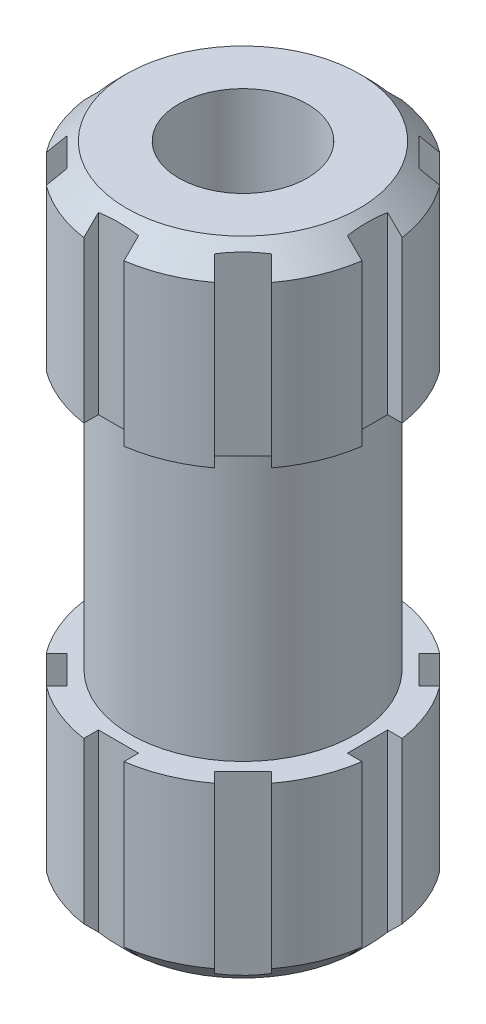
SolidWorks part; units mm, degrees
material "Brass"
ref_plane "Plano frontal" through (0, 0, 0) normal (0, 0, 1) x (1, 0, 0)
ref_plane "Plano superior" through (0, 0, 0) normal (0, 1, 0) x (1, 0, 0)
ref_plane "Plano direito" through (0, 0, 0) normal (1, 0, 0) x (0, 0, -1)
sketch "Esboço2" plane through (0, 0, 0) normal (0, 0, 1) x (1, 0, 0)
  line L0 (0, 0) -> (0, 8) construction
  line L1 (0, 8) -> (1.75, 8)
  line L2 (1.75, 8) -> (1.75, 5.7)
  line L3 (1.75, 5.7) -> (1.4, 5.7)
  line L4 (1.4, 5.7) -> (1.4, 2.3)
  line L5 (1.4, 2.3) -> (1.75, 2.3)
  line L6 (1.75, 2.3) -> (1.75, 0)
  line L7 (0, 0) -> (1.75, 0)
  line L8 (0, 0) -> (0, 8)
  dimension "D1" = 8
  dimension "D2" = 2.3
  dimension "D3" = 3.5
  dimension "D4" = 1.4
revolve "Revolução1" add sketch "Esboço2" angle 360 about L0
chamfer "Chanfro2" distance 0.3 angle 45 2 edges at (0, 0, -1.75) (0, 8, -1.75)
sketch "Esboço7" plane through (0, 8, 0) normal (0, 1, 0) x (1, 0, 0)
  line L0 (0, 1.75) -> (0, -1.75) construction
  line L1 (-0.25, 1.75) -> (0.25, 1.75)
  line L2 (0.25, 1.75) -> (0.25, 1.55)
  line L3 (0.25, 1.55) -> (-0.25, 1.55)
  line L4 (-0.25, 1.55) -> (-0.25, 1.75)
  circle A0 centre (0, 0) radius 1.75 construction
  point P7 (0, 1.75)
  dimension "D1" = 0.2
  dimension "D2" = 0.5
extrude "Corte-extrusão2" cut sketch "Esboço7" against normal up to surface (8 mm away) up to face at (0, 0, -1.45)
pattern_circular "PadrãoCircular1" count 8 over 360 about axis through (0, 0, 0) along (0, 1, 0) of "Corte-extrusão2"
hole_wizard "M6x1.0 Tapped Hole1" [suppressed] positions "Sketch1" profile "Sketch2" tap size "M6x1.0" standard "ANSI Metric"
sketch "Sketch1" plane through (0, 8, 0) normal (0, 1, 0) x (1, 0, 0)
  point P0 (0, 0)
sketch "Sketch2" plane through (0, 8, 0) normal (1, 0, 0) x (0, 0, 1)
  line L0 (0, 0) -> (0, 8)
  line L1 (0, 8) -> (2.5, 8)
  line L2 (2.5, 8) -> (2.5, 0)
  line L5 (2.5, 0) -> (0, 0)
  line L11 (0, -6.35) -> (0, 107.95) construction
  dimension "Thru Tap Drill Dia." = 5
  dimension "Thru Tap Drill Depth" = 8
cosmetic thread "Hole Thread1" [suppressed] parameters "D2"=6
hole_wizard "M3x0.5 Tapped Hole1" [suppressed] positions "Sketch3" profile "Sketch4" tap size "M3x0.5" standard "ANSI Metric"
sketch "Sketch3" plane through (0, 8, 0) normal (0, 1, 0) x (1, 0, 0)
  point P0 (0, 0)
sketch "Sketch4" plane through (0, 8, 0) normal (1, 0, 0) x (0, 0, 1)
  line L0 (0, 0) -> (0, 8)
  line L1 (0, 8) -> (1.25, 8)
  line L2 (1.25, 8) -> (1.25, 0)
  line L5 (1.25, 0) -> (0, 0)
  line L11 (0, -6.35) -> (0, 107.95) construction
  dimension "Thru Tap Drill Dia." = 2.5
  dimension "Thru Tap Drill Depth" = 8
cosmetic thread "Hole Thread2" [suppressed] parameters "D2"=3
hole_wizard "M2x0.4 Tapped Hole1" positions "Sketch5" profile "Sketch6" tap size "M2x0.4" standard "ANSI Metric" end condition through all
sketch "Sketch5" plane through (0, 8, 0) normal (0, 1, 0) x (1, 0, 0)
  point P0 (0, 0)
sketch "Sketch6" plane through (0, 8, 0) normal (1, 0, 0) x (0, 0, 1)
  line L0 (0, 0) -> (0, 8)
  line L1 (0, 8) -> (0.8, 8)
  line L2 (0.8, 8) -> (0.8, 0)
  line L5 (0.8, 0) -> (0, 0)
  line L11 (0, -6.35) -> (0, 107.95) construction
  dimension "Thru Tap Drill Dia." = 1.6
  dimension "Thru Tap Drill Depth" = 8
cosmetic thread "Hole Thread3" parameters "D2"=2
